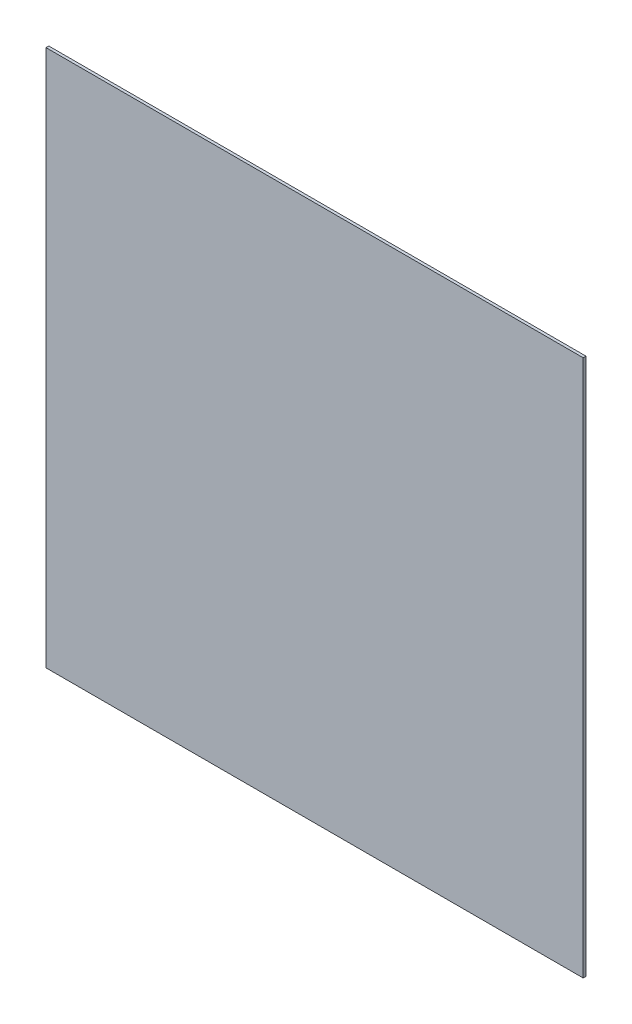
SolidWorks part; units mm, degrees
material "Acrylic (Medium-high impact)"
ref_plane "Front Plane" through (0, 0, 0) normal (0, 0, 1) x (1, 0, 0)
ref_plane "Top Plane" through (0, 0, 0) normal (0, 1, 0) x (1, 0, 0)
ref_plane "Right Plane" through (0, 0, 0) normal (1, 0, 0) x (0, 0, -1)
sketch "Sketch1" plane through (0, 0, 0) normal (0, 0, 1) x (1, 0, 0)
  line L1 (-304.8, -304.8) -> (304.8, -304.8)
  line L2 (-304.8, -304.8) -> (-304.8, 304.8)
  line L3 (-304.8, 304.8) -> (304.8, 304.8)
  line L4 (304.8, -304.8) -> (304.8, 304.8)
  line L5 (-304.8, -304.8) -> (304.8, 304.8) construction
  line L6 (-304.8, 304.8) -> (304.8, -304.8) construction
  point P0 (0, 0)
  dimension "D1" = 609.6
  dimension "D2" = 609.6
extrude "Boss-Extrude1" add sketch "Sketch1" along normal blind 3.175
